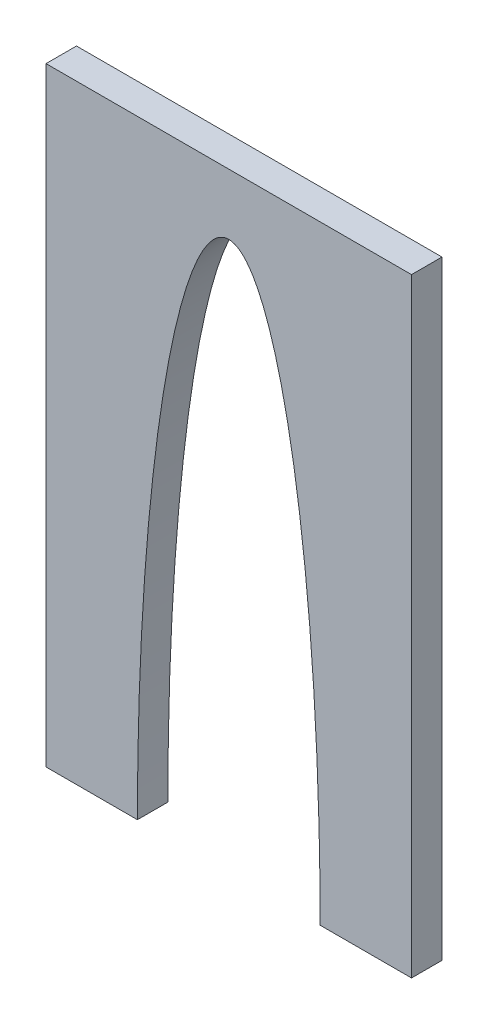
SolidWorks part; units mm, degrees
material "ABS"
ref_plane "Ebene vorne" through (0, 0, 0) normal (0, 0, 1) x (1, 0, 0)
ref_plane "Ebene oben" through (0, 0, 0) normal (0, 1, 0) x (1, 0, 0)
ref_plane "Ebene rechts" through (0, 0, 0) normal (1, 0, 0) x (0, 0, -1)
sketch "Skizze1" plane through (0, 0, 0) normal (0, 0, 1) x (1, 0, 0)
  line L1 (0, 0) -> (12, 0)
  line L2 (0, 0) -> (0, 20)
  line L3 (0, 20) -> (12, 20)
  line L4 (12, 0) -> (12, 20)
  dimension "D1" = 12
  dimension "D2" = 20
extrude "Aufsatz-Linear austragen1" add sketch "Skizze1" along normal blind 1
sketch "Skizze2" plane through (0, 0, 0) normal (0, 0, -1) x (-1, 0, 0)
  line L0 (0, 0) -> (-12, 0) construction
  ellipse E0 centre (-6, 0) end of major axis (-6, 18) minor radius 3
  dimension "D1" = 6
  dimension "15" = 18
extrude "Schnitt-Linear austragen1" cut sketch "Skizze2" against normal through all
